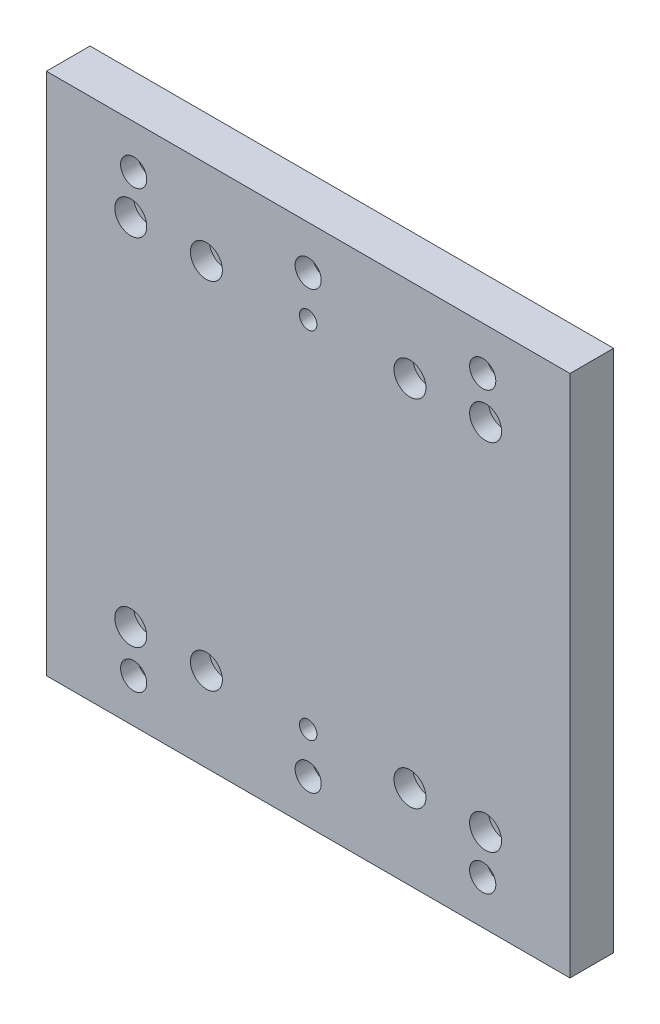
SolidWorks part; units mm, degrees
ref_plane "前视基准面" through (0, 0, 0) normal (0, 0, 1) x (1, 0, 0)
ref_plane "上视基准面" through (0, 0, 0) normal (0, 1, 0) x (1, 0, 0)
ref_plane "右视基准面" through (0, 0, 0) normal (1, 0, 0) x (0, 0, -1)
sketch "草图1" plane through (0, 0, 0) normal (0, 0, 1) x (1, 0, 0)
  line L1 (-90, 90) -> (90, 90)
  line L2 (-90, 90) -> (-90, -90)
  line L3 (-90, -90) -> (90, -90)
  line L4 (90, 90) -> (90, -90)
  dimension "D1" = 180
  dimension "D2" = 180
  dimension "D3" = 90
  dimension "D4" = 90
extrude "凸台-拉伸1" add sketch "草图1" along normal blind 15
sketch "草图2" plane through (0, 0, 15) normal (0, 0, 1) x (1, 0, 0)
  line L0 (-61, 61) -> (-61, -61) construction
  line L1 (-61, 61) -> (61, 61) construction
  line L2 (61, 61) -> (61, -61) construction
  line L3 (61, -61) -> (-61, -61) construction
  line L4 (-35, 61) -> (-35, -61) construction
  line L5 (35, 61) -> (35, -61) construction
  line L6 (0, 61) -> (0, -61) construction
  dimension "D1" = 122
  dimension "D2" = 122
  dimension "D3" = 70
  dimension "D4" = 35
hole_wizard "打孔尺寸根据内六角花形圆柱头螺钉-4.8级的类型1" positions "3D草图1" profile "草图3" counterbore size "M14" standard "Gb" end condition through all
sketch3d "3D草图1"
  point P0 (-61, 61, 15)
  point P5 (35, 61, 15)
  point P8 (-35, 61, 15)
  point P11 (-61, -61, 15)
  point P14 (-35, -61, 15)
  point P17 (35, -61, 15)
  point P20 (61, -61, 15)
  point P23 (61, 61, 15)
sketch "草图3" plane through (-61, 61, 15) normal (1, 0, 0) x (0, -1, 0)
  line L0 (0, 0) -> (0, 15)
  line L1 (0, 15) -> (3.25, 15)
  line L3 (3.25, 15) -> (3.25, 6.5)
  line L4 (3.25, 6.5) -> (5.5, 6.5)
  line L5 (5.5, 6.5) -> (5.5, 0)
  line L7 (5.5, 0) -> (0, 0)
  line L11 (0, -6.35) -> (0, 107.95) construction
  dimension "通孔孔直径" = 6.5
  dimension "通孔孔深度" = 15
  dimension "柱形沉头孔直径" = 11
  dimension "柱形沉头孔深度" = 6.5
hole_wizard "Ø6.0 (6) 直径孔1" positions "3D草图2" profile "草图4" hole size "Ø6.0" standard "Gb" end condition through all
sketch3d "3D草图2"
  point P0 (0, 61, 15)
  point P3 (0, -61, 15)
sketch "草图4" plane through (0, 61, 15) normal (1, 0, 0) x (0, -1, 0)
  line L0 (0, 0) -> (0, 15)
  line L1 (0, 15) -> (3, 15)
  line L2 (3, 15) -> (3, 0)
  line L5 (3, 0) -> (0, 0)
  line L11 (0, -6.35) -> (0, 107.95) construction
  dimension "通孔孔直径" = 6
  dimension "通孔孔深度" = 15
sketch "草图5" plane through (0, 0, 0) normal (0, 0, -1) x (-1, 0, 0)
  line L0 (0, 75) -> (0, -75) construction
  line L1 (-60, 75) -> (60, 75)
  line L2 (-60, 75) -> (-60, -75)
  line L3 (-60, -75) -> (60, -75)
  line L4 (60, 75) -> (60, -75)
  dimension "D1" = 150
  dimension "D2" = 120
  dimension "D3" = 60
  dimension "D4" = 75
hole_wizard "打孔尺寸根据内六角花形圆柱头螺钉-4.8级的类型2" positions "3D草图3" profile "草图6" counterbore size "M14" standard "Gb" end condition through all
sketch3d "3D草图3"
  point P0 (60, 75, 0)
  point P3 (0, 75, 0)
  point P6 (-60, 75, 0)
  point P9 (-60, -75, 0)
  point P12 (0, -75, 0)
  point P15 (60, -75, 0)
sketch "草图6" plane through (60, 75, 0) normal (1, 0, 0) x (0, 1, 0)
  line L0 (0, 0) -> (0, 15)
  line L1 (0, 15) -> (4.5, 15)
  line L3 (4.5, 15) -> (4.5, 9)
  line L4 (4.5, 9) -> (7.5, 9)
  line L5 (7.5, 9) -> (7.5, 0)
  line L7 (7.5, 0) -> (0, 0)
  line L11 (0, -6.35) -> (0, 107.95) construction
  dimension "通孔孔直径" = 9
  dimension "通孔孔深度" = 15
  dimension "柱形沉头孔直径" = 15
  dimension "柱形沉头孔深度" = 9
